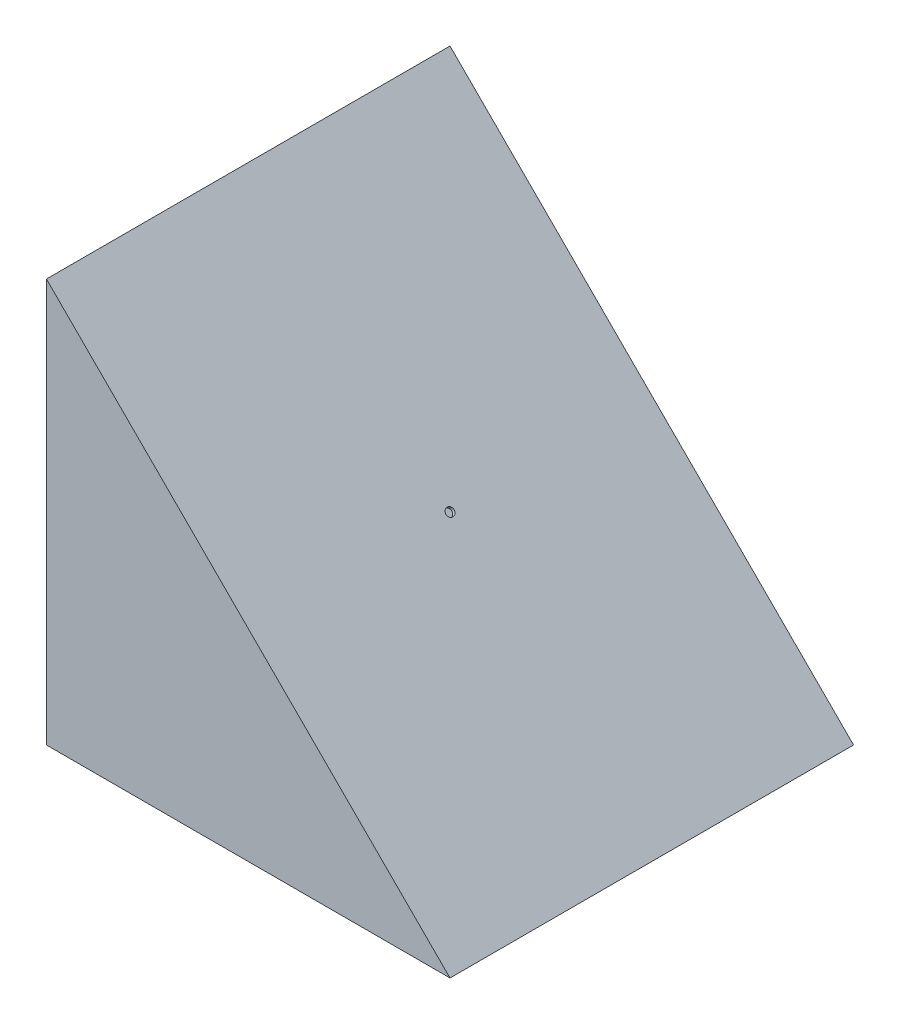
SolidWorks part; units mm, degrees
material "ABS"
ref_plane "Plano frontal" through (0, 0, 0) normal (0, 0, 1) x (1, 0, 0)
ref_plane "Plano superior" through (0, 0, 0) normal (0, 1, 0) x (1, 0, 0)
ref_plane "Plano direito" through (0, 0, 0) normal (1, 0, 0) x (0, 0, -1)
sketch "Esboço1" plane through (0, 0, 0) normal (0, 0, 1) x (1, 0, 0)
  line L0 (0, 0) -> (0, 50)
  line L1 (0, 0) -> (50, 0)
  line L2 (0, 50) -> (50, 0)
  point P2 (0, 0)
  point P6 (0, 0)
  point P7 (0, 0)
  dimension "D1" = 45
  dimension "D2" = 50
extrude "Ressalto-extrusão1" add sketch "Esboço1" along normal blind 50
sketch "Esboço2" plane through (0, 0, 0) normal (0, -1, 0) x (1, 0, 0)
  line L0 (25, 51.7292) -> (25, -3.321) construction
  line L1 (0, 50) -> (50, 50) construction
  line L2 (-5.974, 25) -> (57.1015, 25) construction
  line L3 (0, 50) -> (0, 0) construction
  line L5 (22.4, 19.9) -> (27.6, 19.9)
  line L6 (22.4, 19.9) -> (22.4, 30.1)
  line L7 (22.4, 30.1) -> (27.6, 30.1)
  line L8 (27.6, 19.9) -> (27.6, 30.1)
  line L9 (22.4, 19.9) -> (27.6, 30.1) construction
  line L10 (22.4, 30.1) -> (27.6, 19.9) construction
  line L11 (19.9, 22.4) -> (30.1, 22.4)
  line L12 (19.9, 22.4) -> (19.9, 27.6)
  line L13 (19.9, 27.6) -> (30.1, 27.6)
  line L14 (30.1, 22.4) -> (30.1, 27.6)
  line L15 (19.9, 22.4) -> (30.1, 27.6) construction
  line L16 (19.9, 27.6) -> (30.1, 22.4) construction
  point P4 (25, 50)
  point P9 (0, 25)
  point P10 (0, 0)
  point P11 (0, 0)
  point P12 (25, 25)
  point P17 (25, 25)
  dimension "D1" = 5.2
  dimension "D2" = 10.2
  dimension "D3" = 5.2
  dimension "D4" = 10.2
extrude "Corte-extrusão1" cut sketch "Esboço2" against normal blind 6 contours L6 L13 L8 L7 | L13 L12 L11 L6 | L13 L6 L11 L8 | L11 L14 L13 L8 | L11 L6 L5 L8
sketch "Esboço3" plane through (25, 25, 0) normal (0.7071, 0.7071, 0) x (0, 0, -1)
  line L0 (-25, 37.5194) -> (-25, -37.9906) construction
  line L2 (-50, 35.3553) -> (0, 35.3553) construction
  line L3 (15.7085, 0) -> (-55.1095, 0) construction
  circle A0 centre (-25, 0) radius 0.5
  point P4 (-25, 35.3553)
  point P10 (0, 0)
  point P11 (0, 0)
  dimension "D1" = 1
extrude "Corte-extrusão2" cut sketch "Esboço3" against normal blind 0.4
